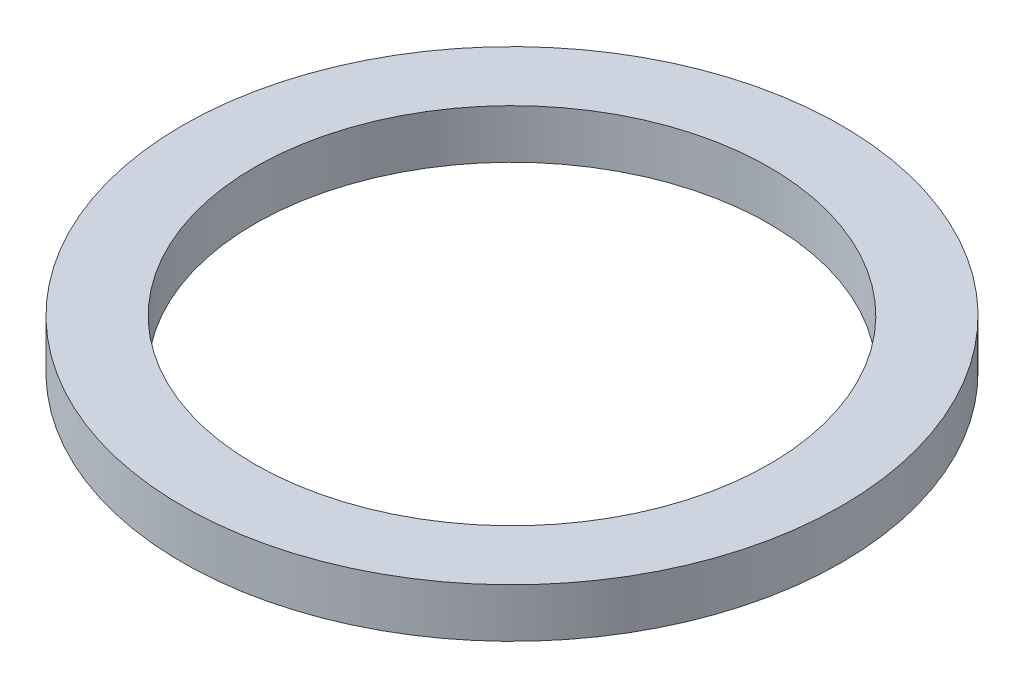
SolidWorks part; units mm, degrees
ref_plane "前基準面" through (0, 0, 0) normal (0, 0, 1) x (1, 0, 0)
ref_plane "上基準面" through (0, 0, 0) normal (0, 1, 0) x (1, 0, 0)
ref_plane "右基準面" through (0, 0, 0) normal (1, 0, 0) x (0, 0, -1)
sketch "草圖1" plane through (0, 0, 0) normal (0, 1, 0) x (1, 0, 0)
  circle A0 centre (0, 0) radius 10.5
  dimension "D1" = 21
extrude "伸長-薄件1" add sketch "草圖1" along normal blind 2 thin
